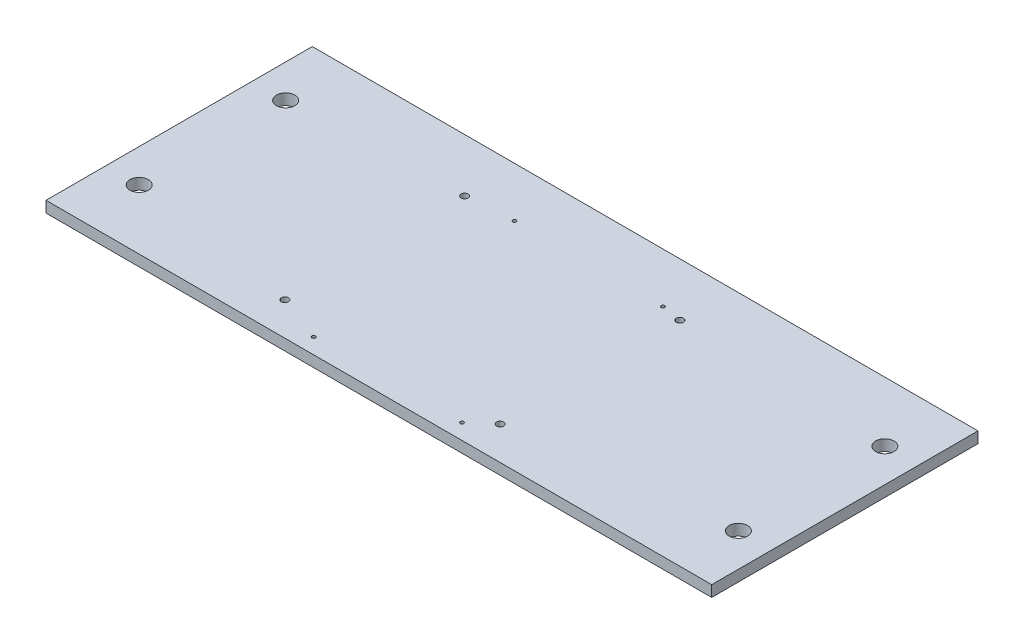
SolidWorks part; units mm, degrees
ref_plane "Front Plane" through (0, 0, 0) normal (0, 0, 1) x (1, 0, 0)
ref_plane "Top Plane" through (0, 0, 0) normal (0, 1, 0) x (1, 0, 0)
ref_plane "Right Plane" through (0, 0, 0) normal (1, 0, 0) x (0, 0, -1)
sketch "Sketch1" plane through (0, 0, 0) normal (0, 1, 0) x (1, 0, 0)
  line L1 (0, 0) -> (300, 0)
  line L2 (0, 0) -> (0, -120)
  line L3 (0, -120) -> (300, -120)
  line L4 (300, 0) -> (300, -120)
  dimension "D1" = 120
  dimension "D2" = 300
extrude "Boss-Extrude1" add sketch "Sketch1" along normal blind 5
sketch "Sketch2" plane through (0, 5, 0) normal (0, 1, 0) x (1, 0, 0)
  line L0 (150, 0) -> (150, -120) construction
  line L1 (300, 0) -> (0, 0) construction
  line L2 (0, -120) -> (300, -120) construction
  line L3 (0, -60) -> (300, -60) construction
  line L4 (0, 0) -> (0, -120) construction
  line L5 (300, -120) -> (300, 0) construction
  circle A0 centre (15, -27) radius 4.15
  circle A1 centre (285, -27) radius 4.15
  circle A2 centre (285, -93) radius 4.15
  circle A3 centre (15, -93) radius 4.15
  dimension "D1" = 8.3
  dimension "D2" = 33
  dimension "D3" = 135
sketch "Sketch3" plane through (0, 5, 0) normal (0, 1, 0) x (1, 0, 0)
  line L0 (0, -120) -> (300, -120) construction
  line L1 (0, 0) -> (0, -120) construction
  line L4 (300, 0) -> (0, 0) construction
  point P0 (113.6419, -22.4976)
  point P1 (113.6419, -112.9946)
  point P2 (180.4745, -112.9946)
  point P3 (180.4745, -22.4976)
  dimension "D1" = 66.8326
  dimension "D2" = 90.497
  dimension "D3" = 7.0054
  dimension "D4" = 90.497
  dimension "D5" = 66.8326
  dimension "D6" = 113.6419
  dimension "D7" = 113.6419
  dimension "D8" = 22.4976
hole_wizard "Tap Drill for M2 Tap1" positions "Sketch4" profile "Sketch5" hole size "M2" standard "ISO" end condition through all
sketch "Sketch4" plane through (0, 5, 0) normal (0, 1, 0) x (1, 0, 0)
  point P0 (113.6419, -112.9946)
  point P3 (180.4745, -112.9946)
  point P6 (180.4745, -22.4976)
  point P9 (113.6419, -22.4976)
sketch "Sketch5" plane through (113.6419, 5, 112.9946) normal (1, 0, 0) x (0, 0, 1)
  line L0 (0, 0) -> (0, 5)
  line L1 (0, 5) -> (0.8, 5)
  line L2 (0.8, 5) -> (0.8, 0)
  line L5 (0.8, 0) -> (0, 0)
  line L11 (0, -6.35) -> (0, 107.95) construction
  dimension "Thru Hole Dia." = 1.6
  dimension "Thru Hole Depth" = 5
sketch "Sketch6" plane through (0, 5, 0) normal (0, 1, 0) x (1, 0, 0)
  line L1 (300, 0) -> (0, 0) construction
  line L2 (0, -120) -> (300, -120) construction
  point P0 (92.6419, -105)
  point P1 (189.6419, -105)
  point P2 (189.6419, -24)
  point P3 (92.6419, -24)
  point P7 (100.6419, -100)
  point P8 (0, 0)
  point P9 (0, 0)
  dimension "D1" = 97
  dimension "D2" = 97
  dimension "D3" = 81
  dimension "D4" = 15
  dimension "D5" = 21
  dimension "D6" = 81
  dimension "D7" = 15
  dimension "D8" = 24
hole_wizard "M3 Clearance Hole1" positions "Sketch7" profile "Sketch8" hole size "M3" standard "ISO" end condition through all
sketch "Sketch7" plane through (0, 5, 0) normal (0, 1, 0) x (1, 0, 0)
  point P0 (92.6419, -105)
  point P3 (92.6419, -24)
  point P6 (189.6419, -24)
  point P9 (189.6419, -105)
sketch "Sketch8" plane through (92.6419, 5, 105) normal (1, 0, 0) x (0, 0, 1)
  line L0 (0, 0) -> (0, 5)
  line L1 (0, 5) -> (1.6, 5)
  line L2 (1.6, 5) -> (1.6, 0)
  line L5 (1.6, 0) -> (0, 0)
  line L11 (0, -6.35) -> (0, 107.95) construction
  dimension "Thru Hole Dia." = 3.2
  dimension "Thru Hole Depth" = 5
extrude "Cut-Extrude1" cut sketch "Sketch2" against normal through all contours A0 | A3 | A1 | A2
